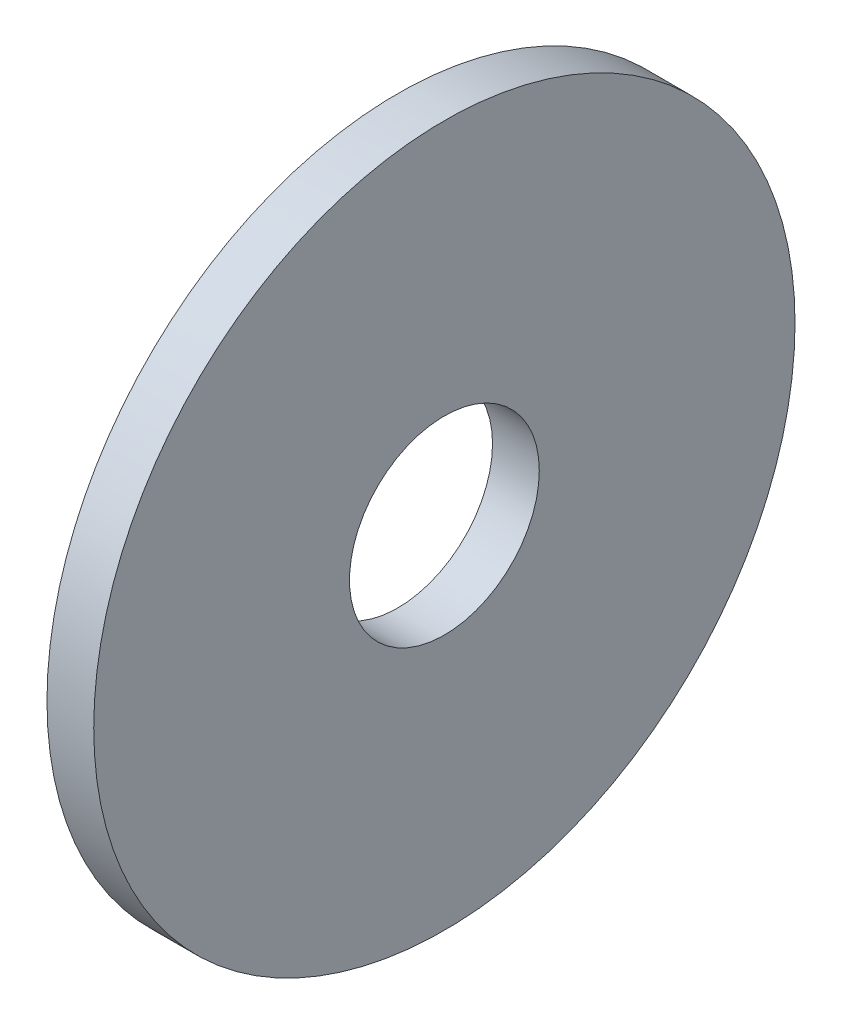
SolidWorks part; units mm, degrees
ref_plane "Front Plane" through (0, 0, 0) normal (0, 0, 1) x (1, 0, 0)
ref_plane "Top Plane" through (0, 0, 0) normal (0, 1, 0) x (1, 0, 0)
ref_plane "Right Plane" through (0, 0, 0) normal (1, 0, 0) x (0, 0, -1)
sketch "Sketch1" plane through (0, 0, 0) normal (1, 0, 0) x (0, 0, -1)
  circle A0 centre (0, 0) radius 9.525
  circle A1 centre (0, 0) radius 2.5781
  dimension "OD" = 19.05
  dimension "ID" = 5.1562
extrude "Boss-Extrude1" add sketch "Sketch1" along normal blind 1.27
